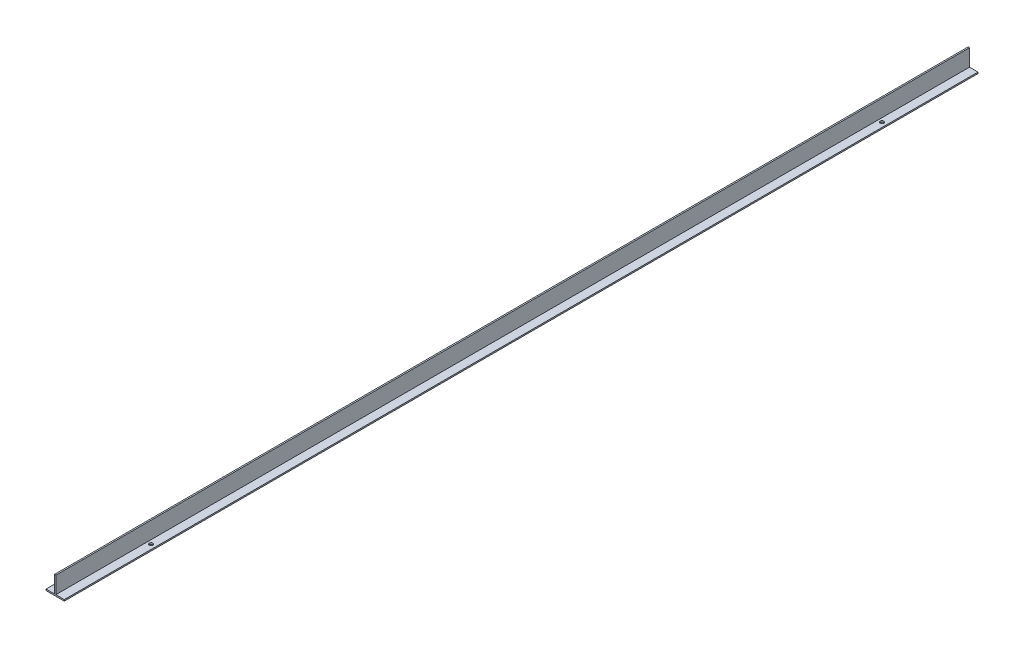
SolidWorks part; units mm, degrees
ref_plane "Спереди" through (0, 0, 0) normal (0, 0, 1) x (1, 0, 0)
ref_plane "Сверху" through (0, 0, 0) normal (0, 1, 0) x (1, 0, 0)
ref_plane "Справа" through (0, 0, 0) normal (1, 0, 0) x (0, 0, -1)
sketch "Эскиз1" plane through (0, 0, 0) normal (0, 0, 1) x (1, 0, 0)
  line L0 (0, 0) -> (0, 20) construction
  line L1 (0.75, 20) -> (-0.75, 20)
  line L2 (-0.75, 20) -> (-0.75, 1.5)
  line L3 (-0.75, 1.5) -> (-10, 1.5)
  line L4 (-10, 1.5) -> (-10, 0)
  line L5 (-10, 0) -> (10, 0)
  line L6 (10, 1.5) -> (10, 0)
  line L7 (0.75, 1.5) -> (10, 1.5)
  line L8 (0.75, 20) -> (0.75, 1.5)
  dimension "D1" = 20
  dimension "D2" = 0.75
  dimension "D3" = 1.5
  dimension "D4" = 10
extrude "Бобышка-Вытянуть1" add sketch "Эскиз1" along normal blind 1000
sketch "Эскиз2" plane through (0, 0, 0) normal (0, -1, 0) x (1, 0, 0)
  line L0 (-10, 1000) -> (10, 1000) construction
  line L1 (10, 1000) -> (10, 0) construction
  line L2 (-10, 1000) -> (-10, 0) construction
  line L3 (-10, 500) -> (10, 500) construction
  circle A0 centre (5, 900) radius 2
  circle A1 centre (-5, 900) radius 2
  circle A2 centre (5, 100) radius 2
  circle A3 centre (-5, 100) radius 2
  dimension "D1" = 100
  dimension "D2" = 4
  dimension "D3" = 5
  dimension "D4" = 5
extrude "Вырез-Вытянуть1" cut sketch "Эскиз2" against normal blind 10
